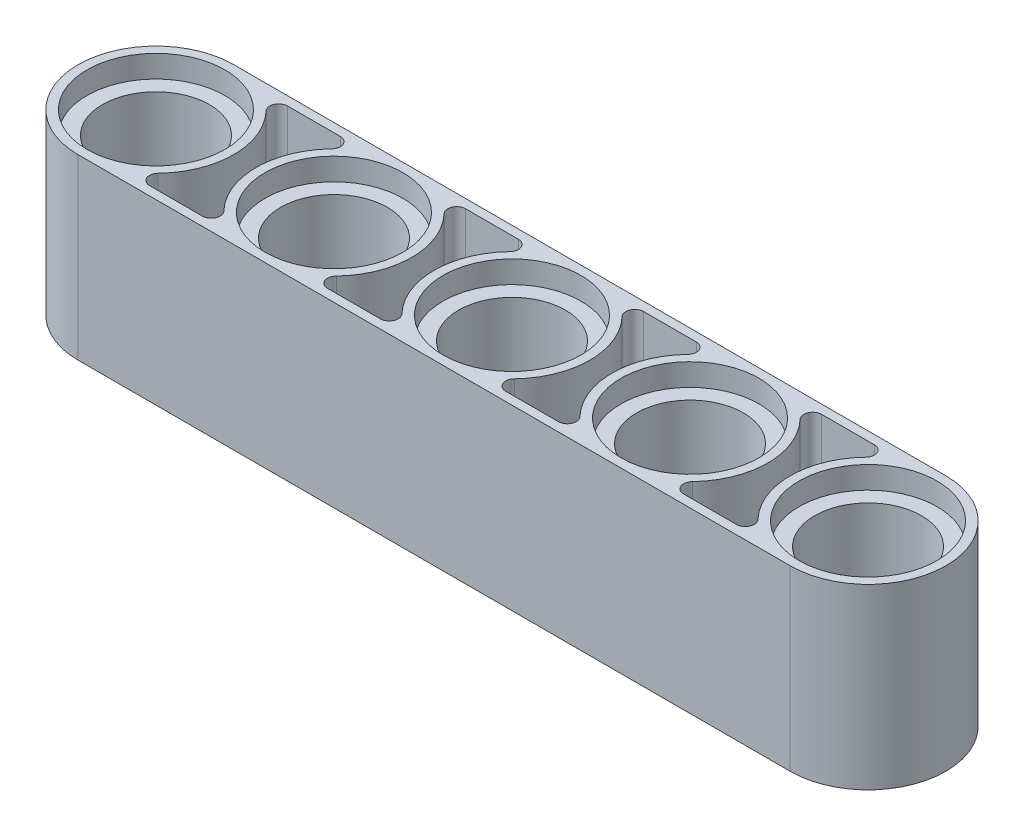
SolidWorks part; units mm, degrees
ref_plane "Front Plane" through (0, 0, 0) normal (0, 0, 1) x (1, 0, 0)
ref_plane "Top Plane" through (0, 0, 0) normal (0, 1, 0) x (1, 0, 0)
ref_plane "Right Plane" through (0, 0, 0) normal (1, 0, 0) x (0, 0, -1)
sketch "Sketch2" plane through (0, 0, 0) normal (0, 1, 0) x (1, 0, 0)
  line L0 (0, 0) -> (32, 0) construction
  line L1 (0, 3.5) -> (32, 3.5)
  line L2 (0, -3.5) -> (32, -3.5)
  arc A0 (0, 3.5) -> (0, -3.5) centre (0, 0) ccw
  arc A1 (32, -3.5) -> (32, 3.5) centre (32, 0) ccw
  point P3 (16, 0)
  point P8 (-3.5, 0)
  point P9 (35.5, 0)
  dimension "D1" = 39
  dimension "D2" = 7
extrude "Boss-Extrude1" add sketch "Sketch2" along normal mid plane 8
sketch "Sketch3" plane through (0, 4, 0) normal (0, 1, 0) x (1, 0, 0)
  circle A0 centre (0, 0) radius 3.1
  dimension "D1" = 6.2
extrude "Cut-Extrude1" cut sketch "Sketch3" against normal blind 1
sketch "Sketch4" plane through (0, -4, 0) normal (0, -1, 0) x (-1, 0, 0)
  circle A0 centre (0, 0) radius 3.1
  dimension "D1" = 6.2
extrude "Cut-Extrude2" cut sketch "Sketch4" against normal blind 1
sketch "Sketch5" plane through (0, -4, 0) normal (0, -1, 0) x (-1, 0, 0)
  circle A0 centre (0, 0) radius 2.4
  dimension "D1" = 4.8
extrude "Cut-Extrude3" cut sketch "Sketch5" against normal through all
pattern_linear "LPattern2" count 5 spacing 8 along (1, 0, 0) of "Cut-Extrude1", "Cut-Extrude2", "Cut-Extrude3"
sketch "Sketch6" plane through (0, 0, 0) normal (0, 1, 0) x (1, 0, 0)
  line L0 (2.8142, 3.1) -> (5.1858, 3.1)
  line L1 (2.8142, -3.1) -> (5.1858, -3.1)
  arc A0 (2.5256, -2.4231) -> (2.5256, 2.4231) centre (0, 0) ccw
  arc A1 (5.4744, 2.4231) -> (5.4744, -2.4231) centre (8, 0) ccw
  arc A6 (5.4744, -2.4231) -> (5.1858, -3.1) centre (5.1858, -2.7) cw
  arc A7 (2.5256, -2.4231) -> (2.8142, -3.1) centre (2.8142, -2.7) ccw
  arc A8 (2.8142, 3.1) -> (2.5256, 2.4231) centre (2.8142, 2.7) ccw
  arc A9 (5.1858, 3.1) -> (5.4744, 2.4231) centre (5.1858, 2.7) cw
  dimension "D1" = 7
  dimension "D2" = 7
  dimension "D3" = 0.4
extrude "Cut-Extrude4" cut sketch "Sketch6" against normal through all both and the other way through all
pattern_linear "LPattern3" count 4 spacing 8 along (1, 0, 0) of "Cut-Extrude4"
